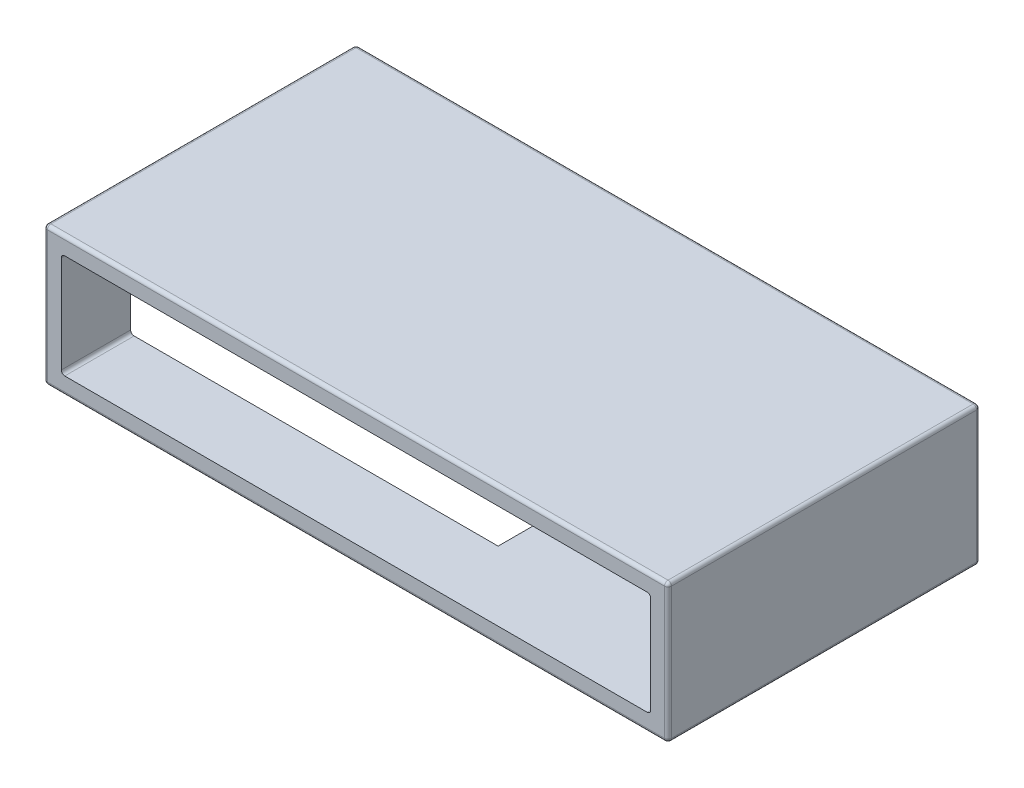
SolidWorks part; units mm, degrees
ref_plane "Front Plane" through (0, 0, 0) normal (0, 0, 1) x (1, 0, 0)
ref_plane "Top Plane" through (0, 0, 0) normal (0, 1, 0) x (1, 0, 0)
ref_plane "Right Plane" through (0, 0, 0) normal (1, 0, 0) x (0, 0, -1)
sketch "Sketch1" plane through (0, 0, 0) normal (0, 0, 1) x (1, 0, 0)
  line L5 (-90, 20) -> (90, 20)
  line L6 (-90, 20) -> (-90, -20)
  line L7 (-90, -20) -> (90, -20)
  line L8 (90, 20) -> (90, -20)
  line L9 (-90, 20) -> (90, -20) construction
  line L10 (-90, -20) -> (90, 20) construction
  line L11 (-85, 15) -> (85, 15)
  line L12 (-85, 15) -> (-85, -15)
  line L13 (-85, -15) -> (85, -15)
  line L14 (85, 15) -> (85, -15)
  line L15 (-85, 15) -> (85, -15) construction
  line L16 (-85, -15) -> (85, 15) construction
  point P0 (0, 0)
  point P7 (0, 0)
  dimension "D1" = 180
  dimension "D2" = 40
  dimension "D3" = 170
  dimension "D4" = 30
extrude "Boss-Extrude1" add sketch "Sketch1" along normal blind 90
fillet "Fillet1" radius 1 16 edges at (90, 0, 0) (90, -20, 45) (0, -20, 0) (90, 0, 90) (0, -20, 90) (-90, 0, 90) (-90, 0, 0) (-90, -20, 45) (90, 20, 45) (0, 20, 0) (0, 20, 90) (-90, 20, 45) (85, 15, 45) (-85, 15, 45) (-85, -15, 45) (85, -15, 45)
sketch "Sketch2" plane through (0, -20, 0) normal (0, -1, 0) x (1, 0, 0)
  line L0 (-89, 70) -> (-89, 20)
  line L1 (-89, 70) -> (21, 70)
  line L2 (-89, 20) -> (21, 20)
  line L3 (21, 70) -> (21, 20)
  line L4 (-89, 89) -> (-89, 1) construction
  line L5 (89, 0) -> (-89, 0) construction
  dimension "D1" = 50
  dimension "D2" = 20
  dimension "D3" = 110
extrude "Cut-Extrude1" cut sketch "Sketch2" against normal blind 25
sketch "Sketch3" plane through (-90, 0, 0) normal (-1, 0, 0) x (0, 0, 1)
  line L0 (20, -20) -> (70, -20)
  line L1 (20, -20) -> (20, 10)
  line L2 (70, -20) -> (70, 10)
  line L3 (20, 10) -> (70, 10)
  line L4 (70, -20) -> (20, -20) construction
  line L5 (89, -20) -> (70, -20) construction
  line L6 (0, -19) -> (0, 19) construction
  dimension "D1" = 30
  dimension "D2" = 50
  dimension "D3" = 20
extrude "Cut-Extrude2" cut sketch "Sketch3" against normal blind 16
sketch "Sketch4" plane through (-90, 0, 0) normal (-1, 0, 0) x (0, 0, 1)
  line L0 (45, -20) -> (45, 20) construction
  line L1 (20, -20) -> (70, -20) construction
  line L2 (1, 20) -> (89, 20) construction
  line L3 (45, -6.5921) -> (10, -6.5921) construction
  circle A0 centre (10, -6.5921) radius 2.5
  circle A1 centre (80, -6.5921) radius 2.5
  dimension "D1" = 5
  dimension "D2" = 35
extrude "Cut-Extrude3" cut sketch "Sketch4" against normal blind 1
